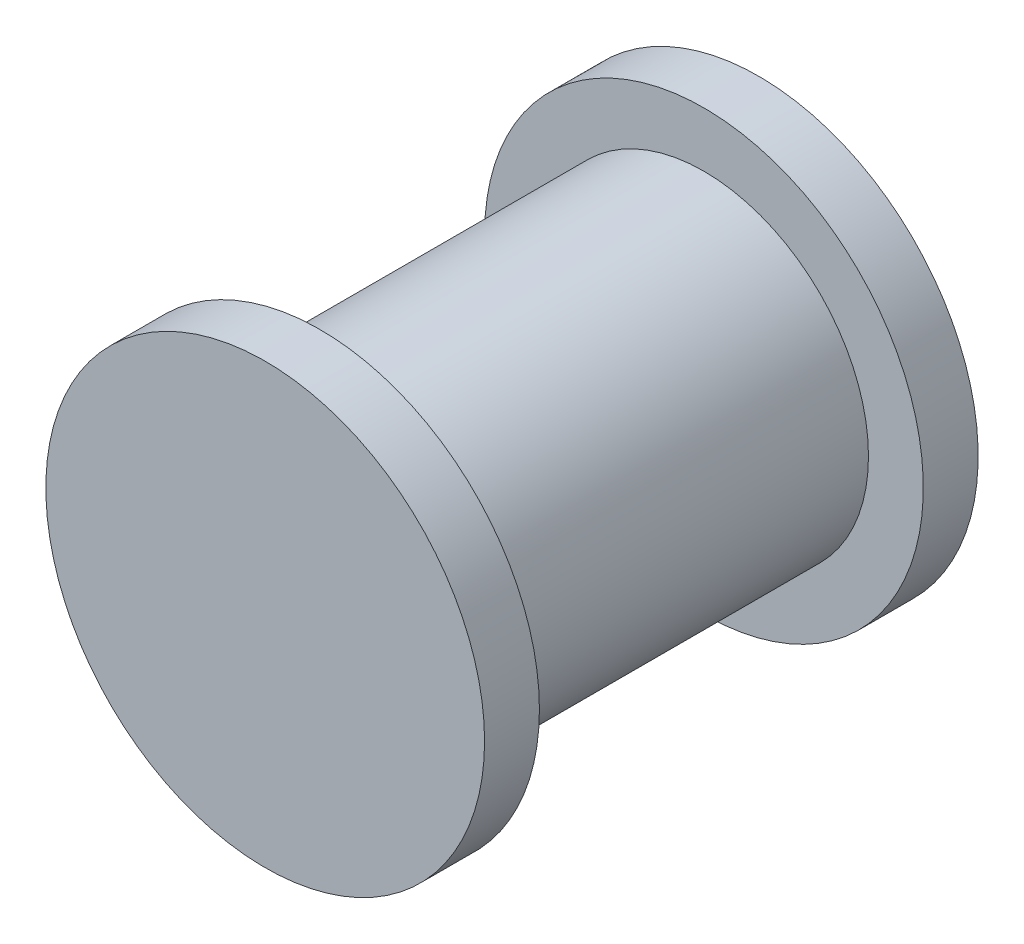
SolidWorks part; units mm, degrees
material "Cast Alloy Steel"
ref_plane "Front Plane" through (0, 0, 0) normal (0, 0, 1) x (1, 0, 0)
ref_plane "Top Plane" through (0, 0, 0) normal (0, 1, 0) x (1, 0, 0)
ref_plane "Right Plane" through (0, 0, 0) normal (1, 0, 0) x (0, 0, -1)
sketch "Sketch1" plane through (0, 0, 0) normal (0, 0, 1) x (1, 0, 0)
  circle A0 centre (0, 0) radius 7.62
  dimension "D1" = 15.24
extrude "Boss-Extrude1" add sketch "Sketch1" along normal blind 17.78
sketch "Sketch2" plane through (0, 0, 17.78) normal (0, 0, 1) x (1, 0, 0)
  circle A0 centre (0, 0) radius 10.16
  dimension "D2" = 20.32
extrude "Boss-Extrude2" add sketch "Sketch2" along normal blind 2.54
sketch "Sketch3" plane through (0, 0, 0) normal (0, 0, -1) x (-1, 0, 0)
  circle A0 centre (0, 0) radius 10.16
  dimension "D2" = 20.32
extrude "Boss-Extrude3" add sketch "Sketch3" along normal blind 2.54
